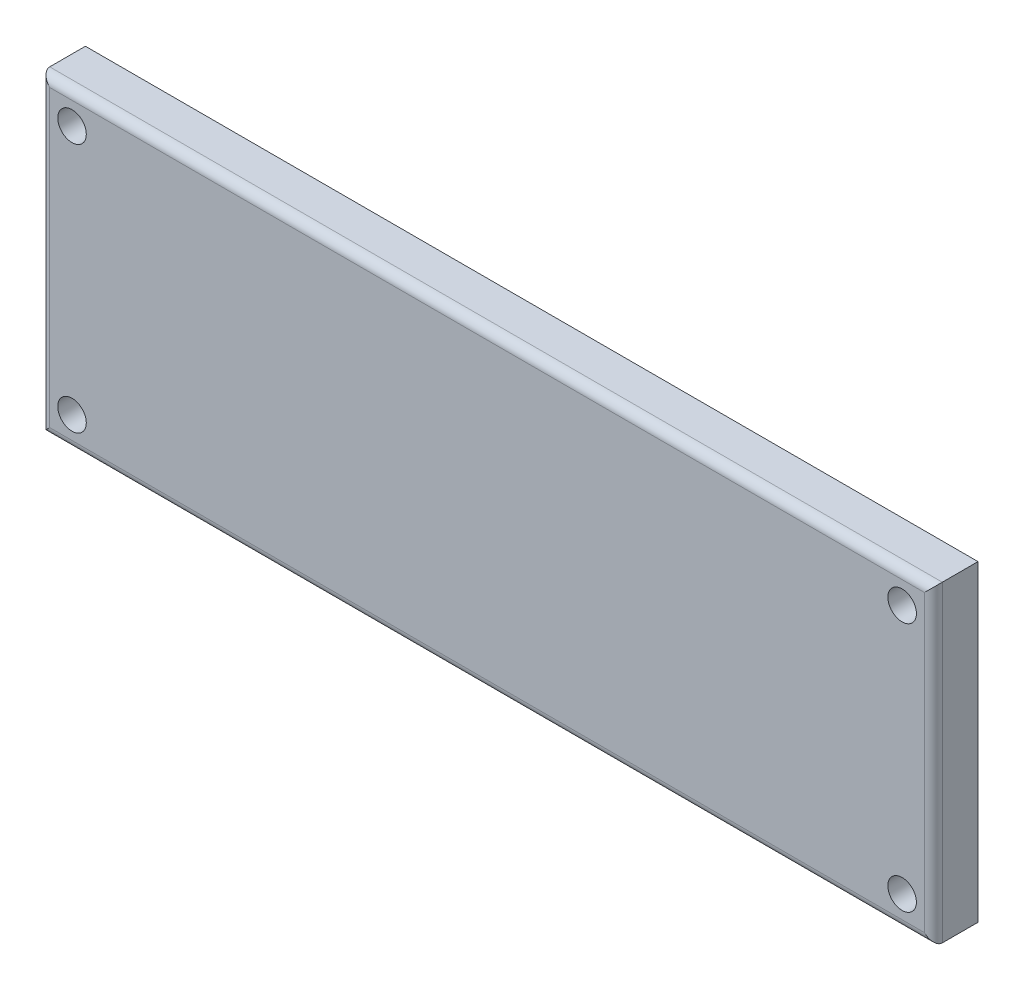
SolidWorks part; units mm, degrees
ref_plane "Front Plane" through (0, 0, 0) normal (0, 0, 1) x (1, 0, 0)
ref_plane "Top Plane" through (0, 0, 0) normal (0, 1, 0) x (1, 0, 0)
ref_plane "Right Plane" through (0, 0, 0) normal (1, 0, 0) x (0, 0, -1)
sketch "Sketch1" plane through (0, 0, 0) normal (0, 0, 1) x (1, 0, 0)
  line L1 (50, 17.5) -> (-50, 17.5)
  line L2 (50, 17.5) -> (50, -17.5)
  line L3 (50, -17.5) -> (-50, -17.5)
  line L4 (-50, 17.5) -> (-50, -17.5)
  line L5 (50, 17.5) -> (-50, -17.5) construction
  line L6 (50, -17.5) -> (-50, 17.5) construction
  point P0 (0, 0)
  dimension "D1" = 35
  dimension "D2" = 100
extrude "Boss-Extrude1" add sketch "Sketch1" along normal blind 5
sketch "Sketch2" plane through (0, 0, 5) normal (0, 0, 1) x (1, 0, 0)
  line L0 (50, 17.5) -> (-50, 17.5) construction
  line L1 (-50, 17.5) -> (-50, -17.5) construction
  line L2 (-50, -17.5) -> (50, -17.5) construction
  line L3 (50, -17.5) -> (50, 17.5) construction
  circle A0 centre (-46.5, 14) radius 1.6
  circle A1 centre (-46.5, -14) radius 1.6
  circle A2 centre (46.5, 14) radius 1.6
  circle A3 centre (46.5, -14) radius 1.6
  point P16 (0, 0)
  point P17 (0, 0)
  dimension "D1" = 3.2
  dimension "D4" = 3.2
  dimension "D7" = 3.2
  dimension "D10" = 3.2
  dimension "D2" = 3.5
  dimension "D3" = 3.5
  dimension "D5" = 3.5
  dimension "D6" = 3.5
  dimension "D8" = 3.5
  dimension "D9" = 3.5
extrude "Cut-Extrude1" cut sketch "Sketch2" against normal blind 5
fillet "Fillet1" radius 1 4 edges at (50, 0, 5) (0, -17.5, 5) (-50, 0, 5) (0, 17.5, 5)
